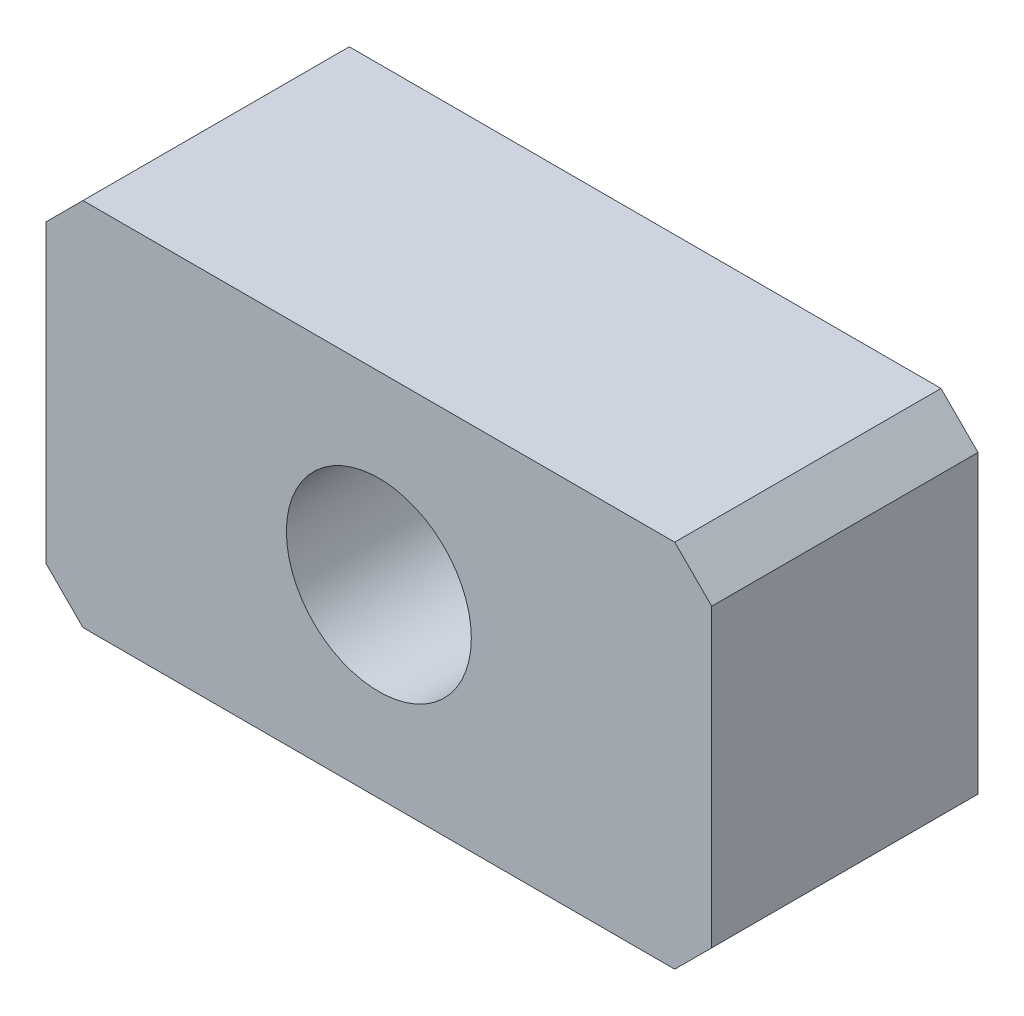
SolidWorks part; units mm, degrees
ref_plane "Front Plane" through (0, 0, 0) normal (0, 0, 1) x (1, 0, 0)
ref_plane "Top Plane" through (0, 0, 0) normal (0, 1, 0) x (1, 0, 0)
ref_plane "Right Plane" through (0, 0, 0) normal (1, 0, 0) x (0, 0, -1)
sketch "Sketch1" plane through (0, 0, 0) normal (0, 0, 1) x (1, 0, 0)
  line L0 (-8, 5) -> (-9, 4)
  line L1 (-9, -5) -> (9, -5)
  line L2 (-9, -5) -> (-9, 5)
  line L3 (-9, 5) -> (9, 5)
  line L4 (9, -5) -> (9, 5)
  line L5 (-9, -5) -> (9, 5) construction
  line L6 (-9, 5) -> (9, -5) construction
  line L7 (0, 0) -> (-50000, 0) construction
  line L8 (0, 0) -> (0, 50000) construction
  line L9 (-8, -5) -> (-9, -4)
  line L10 (8, -5) -> (9, -4)
  line L11 (8, 5) -> (9, 4)
  point P0 (0, 0)
  dimension "D1" = 10
  dimension "D2" = 18
  dimension "D3" = 1
  dimension "D4" = 1
extrude "Boss-Extrude1" add sketch "Sketch1" along normal blind 7.2 contours L11 L3 L0 L2 L9 L1 L10 L4
sketch "Sketch2" plane through (0, 0, 7.2) normal (0, 0, 1) x (1, 0, 0)
  circle A0 centre (0, 0) radius 2.5
  dimension "D1" = 5
extrude "Cut-Extrude1" cut sketch "Sketch2" against normal blind 10
